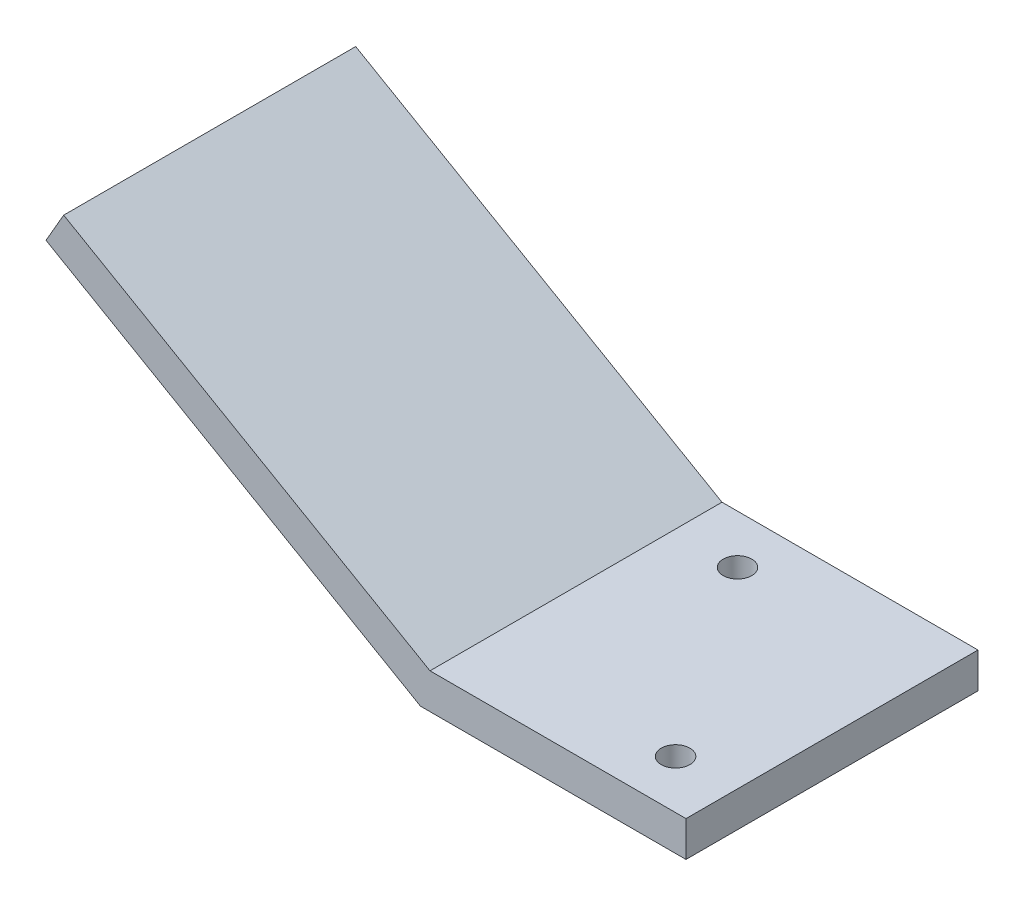
SolidWorks part; units mm, degrees
ref_plane "Front Plane" through (0, 0, 0) normal (0, 0, 1) x (1, 0, 0)
ref_plane "Top Plane" through (0, 0, 0) normal (0, 1, 0) x (1, 0, 0)
ref_plane "Right Plane" through (0, 0, 0) normal (1, 0, 0) x (0, 0, -1)
sketch "Sketch1" plane through (0, 0, 0) normal (0, 1, 0) x (1, 0, 0)
  line L1 (-25, 11.5) -> (25, 11.5)
  line L2 (-25, 11.5) -> (-25, -11.5)
  line L3 (-25, -11.5) -> (25, -11.5)
  line L4 (25, 11.5) -> (25, -11.5)
  line L5 (-25, 11.5) -> (25, -11.5) construction
  line L6 (-25, -11.5) -> (25, 11.5) construction
  point P0 (0, 0)
  dimension "D1" = 23
  dimension "D2" = 50
extrude "Boss-Extrude1" add sketch "Sketch1" along normal blind 20
sketch "Sketch2" plane through (0, 0, 11.5) normal (0, 0, 1) x (1, 0, 0)
  line L0 (25, 4) -> (1.0718, 4)
  line L1 (25, 20) -> (25, 0) construction
  line L2 (1.0718, 4) -> (-25, 19.0526)
  line L3 (-25, 20) -> (-25, 0) construction
  line L4 (-25, 0) -> (25, 0) construction
  line L5 (-25, 0) -> (0, 0)
  line L6 (-25, 14.4338) -> (0, 0)
  line L7 (-25, 19.0526) -> (-25, 20)
  line L8 (-25, 20) -> (25, 20)
  line L9 (25, 20) -> (25, 4)
  line L10 (-25, 20) -> (-25, 19.0526)
  line L11 (-25, 14.4338) -> (-25, 0)
  dimension "D1" = 150
  dimension "D2" = 4
  dimension "D5" = 0
extrude "Cut-Extrude3" cut sketch "Sketch2" against normal blind 30
sketch "Sketch4" plane through (0, 0, 11.5) normal (0, 0, 1) x (1, 0, 0)
  line L0 (-25, 14.4338) -> (-23, 17.8979)
  line L1 (1.0718, 4) -> (-25, 19.0526) construction
  line L2 (-25, 14.4338) -> (0, 0) construction
  line L3 (-23, 17.8979) -> (-25, 19.0526)
  line L4 (-25, 19.0526) -> (-25, 14.4338)
  dimension "D1" = 90
extrude "Cut-Extrude4" cut sketch "Sketch4" against normal blind 30
sketch "Sketch9" plane through (-25, 14.4338, 0) normal (-0.866, 0.5, 0) x (0, 0, 1)
  line L0 (-11.5, 4) -> (11.5, 4)
  line L1 (11.5, 4) -> (11.5, 0)
  line L2 (11.5, 0) -> (-11.5, 0)
  line L3 (-11.5, 0) -> (-11.5, 4)
extrude "Boss-Extrude2" add sketch "Sketch9" along normal blind 20
sketch "Sketch11" plane through (0, 0, -11.5) normal (0, 0, -1) x (-1, 0, 0)
  line L0 (-25, 4) -> (-1.0718, 4)
  line L1 (-1.0718, 4) -> (40.3205, 27.8979)
  line L2 (40.3205, 27.8979) -> (42.3205, 24.4338)
  line L3 (42.3205, 24.4338) -> (0, 0)
  line L4 (0, 0) -> (-25, 0)
  line L5 (-25, 0) -> (-25, 4)
extrude "Boss-Extrude3" add sketch "Sketch11" along normal blind 10
sketch "Sketch17" plane through (0, 0, -21.5) normal (0, 0, -1) x (-1, 0, 0)
  line L0 (2.1062, 5.8348) -> (4.1062, 2.3707)
  line L1 (40.3205, 27.8979) -> (-1.0718, 4) construction
  line L2 (0, 0) -> (42.3205, 24.4338) construction
  line L3 (4.1062, 2.3707) -> (-16.99, -10.6506)
  line L4 (-16.99, -10.6506) -> (-27.424, -10.6506)
  line L5 (-27.424, -10.6506) -> (-28.8305, 8.5324)
  line L6 (-28.8305, 8.5324) -> (-0.4365, 9.7305)
  line L7 (-0.4365, 9.7305) -> (2.1062, 5.8348)
sketch "Sketch22" plane through (25, 0, 0) normal (1, 0, 0) x (0, 0, -1)
  line L0 (-11.5, 4) -> (21.5, 4)
  line L1 (21.5, 4) -> (21.5, 0)
  line L2 (21.5, 0) -> (-11.5, 0)
  line L3 (-11.5, 0) -> (-11.5, 4)
extrude "Boss-Extrude4" add sketch "Sketch22" along normal blind 5
sketch "Sketch23" plane through (0, 0, 0) normal (0, -1, 0) x (1, 0, 0)
  line L0 (0, -5) -> (30, -5) construction
  line L1 (0, -21.5) -> (0, 11.5) construction
  line L2 (30, 11.5) -> (30, -21.5) construction
  line L3 (27.6222, -20.3) -> (27.6222, 10.3)
  line L4 (27.6222, 10.3) -> (4.0222, 10.3)
  line L5 (4.0222, 10.3) -> (4.0222, -20.3)
  line L6 (27.6222, -20.3) -> (4.0222, -20.3)
  line L7 (27.6222, 6) -> (23.3222, 6)
  line L8 (23.3222, 6) -> (23.3222, 10.3)
  line L9 (4.0222, -16) -> (8.3222, -16)
  line L10 (8.3222, -16) -> (8.3222, -20.3)
  circle A0 centre (23.3222, 6) radius 1.62
  circle A1 centre (8.3222, -16) radius 1.62
  point P11 (27.6222, -5)
  point P12 (4.0222, -5)
  dimension "D7" = 3.24
  dimension "D8" = 3.24
  dimension "D1" = 23.6
  dimension "D2" = 15.3
  dimension "D3" = 4.3
  dimension "D4" = 4.3
  dimension "D5" = 4.3
  dimension "D6" = 4.3
extrude "Cut-Extrude7" cut sketch "Sketch23" against normal blind 5 contours L8 A0 L7 | L7 A0 L8 | L10 A1 L9 | L9 A1 L10
sketch "Sketch26" plane through (0, 0, 0) normal (-0.5, -0.866, 0) x (0.866, -0.5, 0)
  line L0 (-48.8675, -5) -> (0, -5) construction
  line L1 (-48.8675, -21.5) -> (-48.8675, 11.5) construction
  line L2 (0, -21.5) -> (0, 11.5) construction
  line L3 (-10, -10) -> (-10, 0)
  line L4 (-10, 0) -> (-40, 0)
  line L5 (-10, -10) -> (-40, -10)
  line L6 (-40, 0) -> (-40, -10)
  point P11 (-10, -5)
  dimension "D1" = 10
  dimension "D2" = 5
  dimension "D3" = 30
extrude "Boss-Extrude5" add sketch "Sketch26" along normal blind 10
sketch "Sketch28" plane through (-5, -8.6603, 0) normal (-0.5, -0.866, 0) x (0.866, -0.5, 0)
  line L3 (-10, -14) -> (-10, 4)
  line L4 (-10, 4) -> (-40, 4)
  line L5 (-40, 4) -> (-40, -14)
  line L6 (-10, -14) -> (-40, -14)
extrude "Boss-Extrude6" add sketch "Sketch28" against normal blind 4
